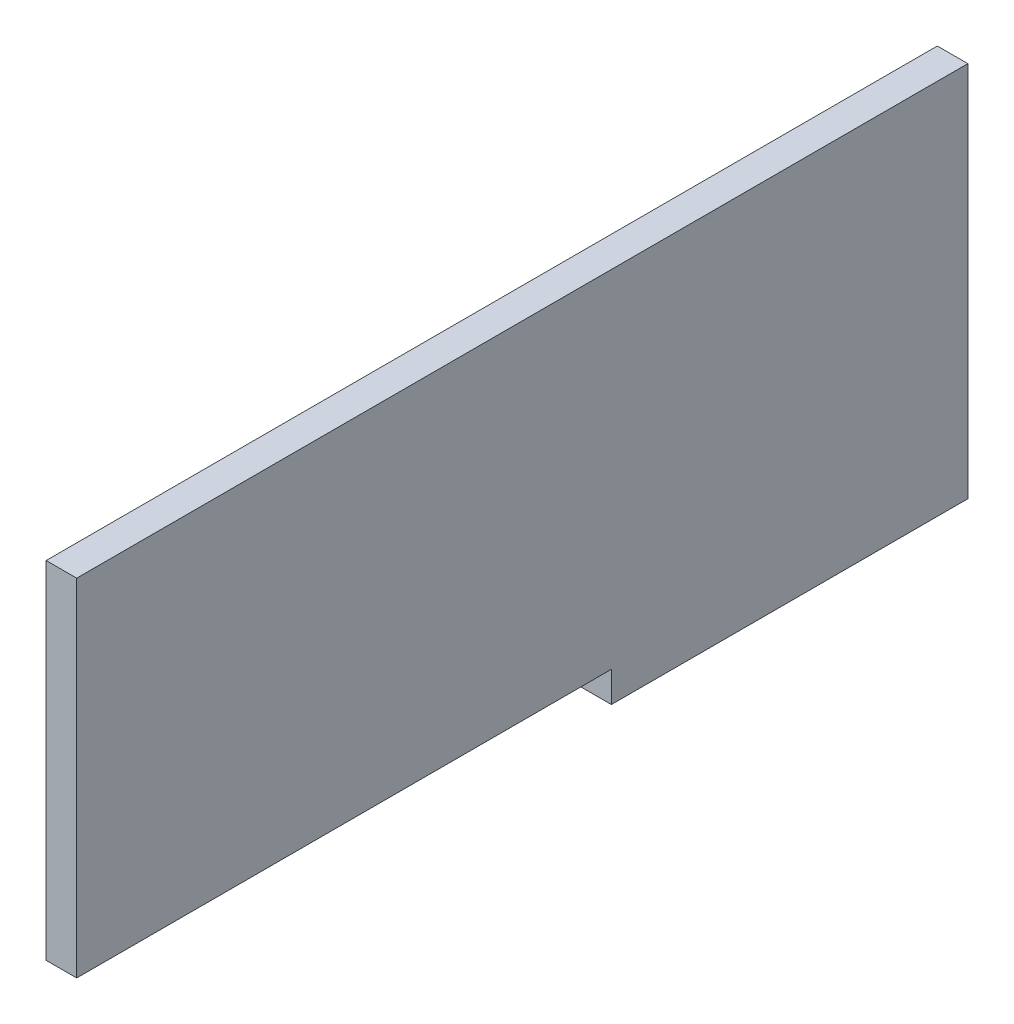
SolidWorks part; units mm, degrees
ref_plane "Front Plane" through (0, 0, 0) normal (0, 0, 1) x (1, 0, 0)
ref_plane "Top Plane" through (0, 0, 0) normal (0, 1, 0) x (1, 0, 0)
ref_plane "Right Plane" through (0, 0, 0) normal (1, 0, 0) x (0, 0, -1)
sketch "Sketch2" plane through (0, 0, 0) normal (1, 0, 0) x (0, 0, -1)
  line L1 (-87.5, -34) -> (17.5, -34)
  line L2 (-87.5, -34) -> (-87.5, 34)
  line L3 (-87.5, 34) -> (87.5, 34)
  line L4 (87.5, -34) -> (87.5, 34)
  line L5 (-87.5, -34) -> (87.5, 34) construction
  line L6 (-87.5, 34) -> (87.5, -34) construction
  line L8 (87.5, -34) -> (87.5, -40)
  line L9 (87.5, -40) -> (17.5, -40)
  line L10 (17.5, -34) -> (17.5, -40)
  point P0 (0, 0)
  dimension "D1" = 175
  dimension "D2" = 68
  dimension "D3" = 70
  dimension "D4" = 6
extrude "Boss-Extrude1" add sketch "Sketch2" along normal blind 6
